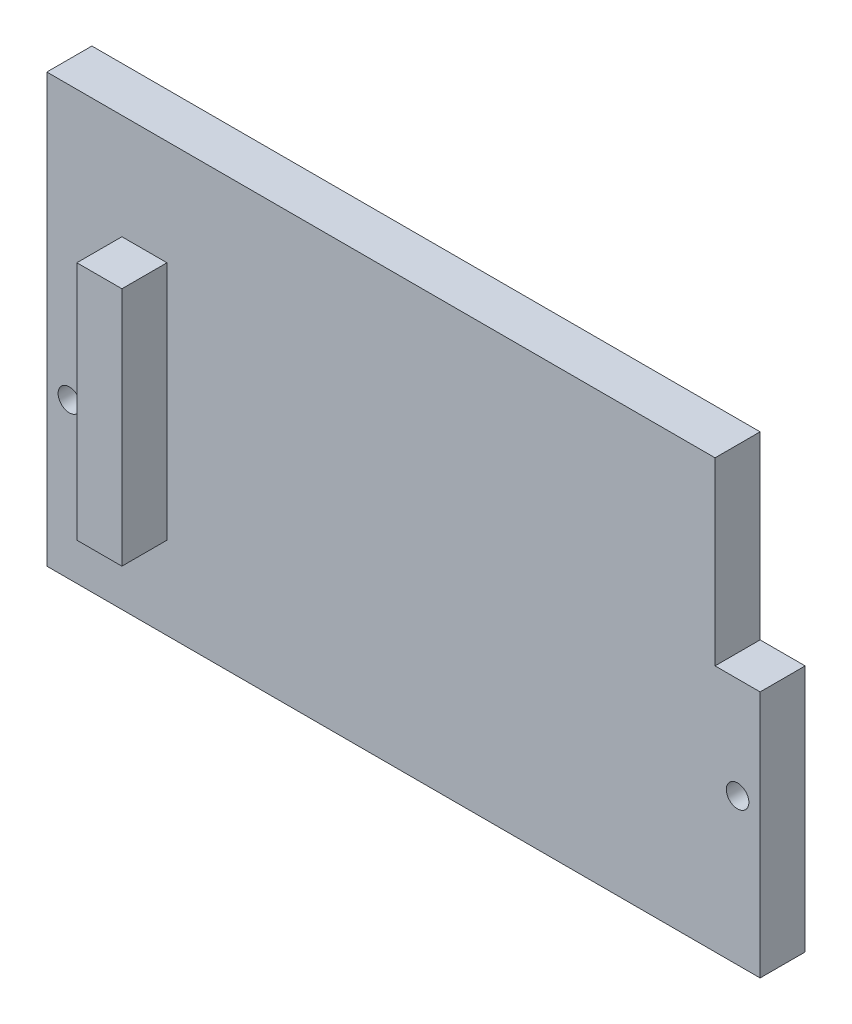
SolidWorks part; units mm, degrees
ref_plane "Front Plane" through (0, 0, 0) normal (0, 0, 1) x (1, 0, 0)
ref_plane "Top Plane" through (0, 0, 0) normal (0, 1, 0) x (1, 0, 0)
ref_plane "Right Plane" through (0, 0, 0) normal (1, 0, 0) x (0, 0, -1)
sketch "Sketch1" plane through (0, 0, 0) normal (0, 0, 1) x (1, 0, 0)
  line L1 (-47.5, -28.5) -> (47.5, -28.5)
  line L2 (-47.5, -28.5) -> (-47.5, 28.5)
  line L3 (-47.5, 28.5) -> (41.5, 28.5)
  line L4 (47.5, -28.5) -> (47.5, 4.5)
  line L5 (-47.5, -28.5) -> (41.5, 24.9) construction
  line L6 (-47.5, 28.5) -> (47.5, -28.5) construction
  line L9 (47.5, 4.5) -> (41.5, 4.5)
  line L10 (41.5, 28.5) -> (41.5, 4.5)
  circle A0 centre (44.5, -9) radius 1.5
  circle A1 centre (-44.5, -7.8128) radius 1.5
  point P0 (0, 0)
  dimension "D7" = 13.5
  dimension "D6" = 3
  dimension "D9" = 3
  dimension "D10" = 3
  dimension "D1" = 3.6
  dimension "D2" = 57
  dimension "D3" = 33
  dimension "D4" = 89
  dimension "D5" = 95
  dimension "D8" = 3
  dimension "D11" = 36.3128
extrude "Boss-Extrude2" add sketch "Sketch1" along normal blind 6
sketch "Sketch3" plane through (0, 0, 6) normal (0, 0, 1) x (1, 0, 0)
  line L0 (41.5, 28.5) -> (-47.5, 28.5) construction
  line L1 (-37.5, 14.5) -> (-31.5, 14.5)
  line L2 (-37.5, 14.5) -> (-37.5, -17.5)
  line L3 (-37.5, -17.5) -> (-31.5, -17.5)
  line L4 (-31.5, 14.5) -> (-31.5, -17.5)
  line L5 (-47.5, 28.5) -> (-47.5, -28.5) construction
  dimension "D1" = 6
  dimension "D2" = 32
  dimension "D3" = 46
  dimension "D4" = 16
extrude "Boss-Extrude3" add sketch "Sketch3" along normal blind 6
